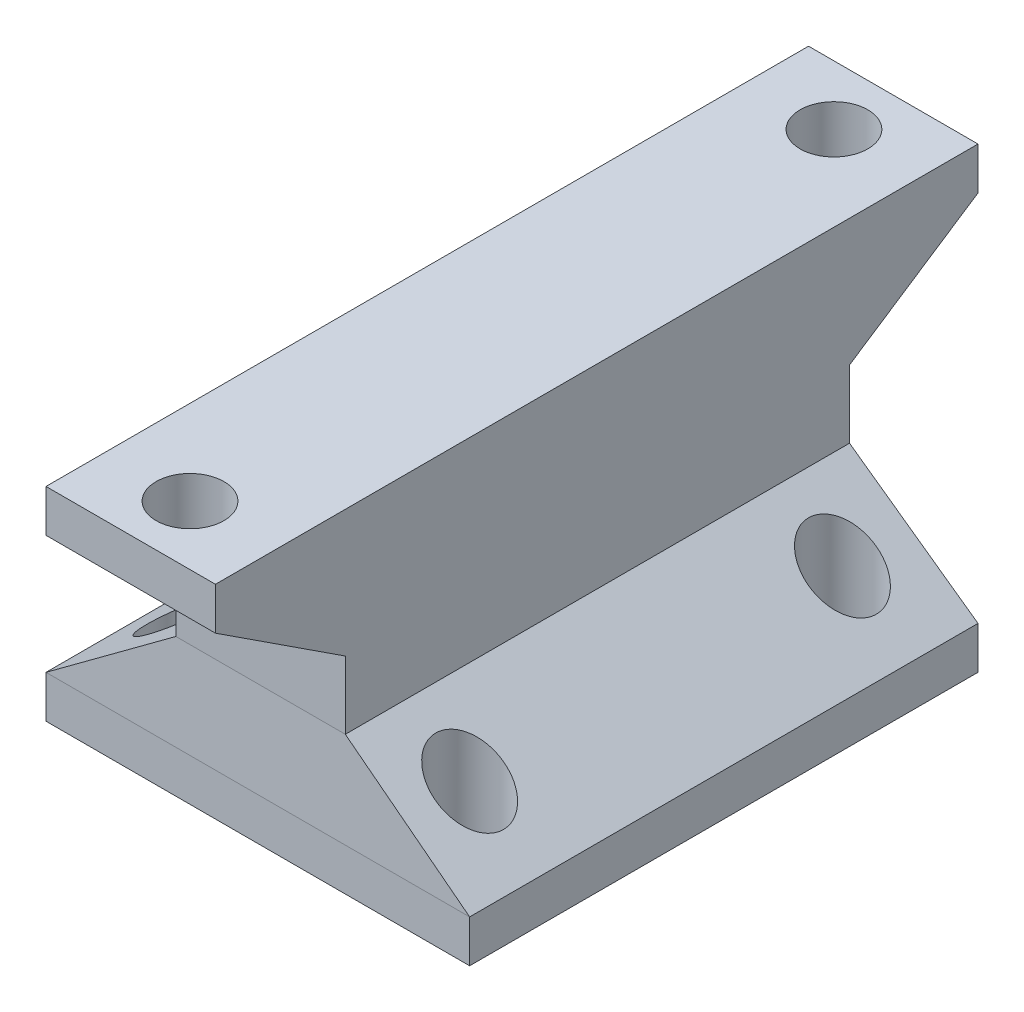
SolidWorks part; units mm, degrees
ref_plane "Front Plane" through (0, 0, 0) normal (0, 0, 1) x (1, 0, 0)
ref_plane "Top Plane" through (0, 0, 0) normal (0, 1, 0) x (1, 0, 0)
ref_plane "Right Plane" through (0, 0, 0) normal (1, 0, 0) x (0, 0, -1)
sketch "Sketch1" plane through (0, 0, 0) normal (0, 1, 0) x (1, 0, 0)
  line L1 (-10, 45) -> (10, 45)
  line L2 (-10, 45) -> (-10, -45)
  line L3 (-10, -45) -> (10, -45)
  line L4 (10, 45) -> (10, -45)
  line L5 (-10, 45) -> (10, -45) construction
  line L6 (-10, -45) -> (10, 45) construction
  point P0 (0, 0)
extrude "Boss-Extrude1" add sketch "Sketch1" along normal blind 5
sketch "Sketch2" plane through (10, 0, 0) normal (1, 0, 0) x (0, 0, -1)
  line L0 (-29.6724, -9.9997) -> (-45, 0)
  line L1 (-45, 0) -> (45, 0)
  line L5 (29.8362, -9.9997) -> (45, 0)
  line L6 (29.8362, -9.9997) -> (-29.6724, -9.9997)
  line L7 (0, 0) -> (0.0819, -9.9997)
  line M7 (-45, 0) -> (45, 0)
extrude "Boss-Extrude2" add sketch "Sketch2" against normal blind 20 contours L7 L0 L6 M7 | L1 L7 L6 L5
ref_plane "Plane1" through (0, -28.9997, 0) normal (0, -1, 0) x (-1, 0, 0)
sketch "Sketch3" plane through (0, -28.9997, 0) normal (0, -1, 0) x (-1, 0, 0)
  line L1 (-25, 30) -> (25, 30)
  line L2 (-25, 30) -> (-25, -30)
  line L3 (-25, -30) -> (25, -30)
  line L4 (25, 30) -> (25, -30)
  line L5 (-25, 30) -> (25, -30) construction
  line L6 (-25, -30) -> (25, 30) construction
  point P0 (0, 0)
extrude "Boss-Extrude3" add sketch "Sketch3" along normal blind 5 separate body
sketch "Sketch4" plane through (0, -33.9997, 0) normal (0, -1, 0) x (1, 0, 0)
  line L1 (-25, 30) -> (-17.08, 30)
  line L2 (-25, 30) -> (-25, 22)
  line L3 (-25, 22) -> (-17.08, 22)
  line L4 (-17.08, 30) -> (-17.08, 22)
  line L5 (25, 30) -> (17, 30)
  line L6 (25, 30) -> (25, 22)
  line L7 (25, 22) -> (17, 22)
  line L8 (17, 30) -> (17, 22)
  line L9 (-25, -30) -> (-17, -30)
  line L10 (-25, -30) -> (-25, -22)
  line L11 (-25, -22) -> (-17, -22)
  line L12 (-17, -30) -> (-17, -22)
  line L13 (25, -30) -> (17, -30)
  line L14 (25, -30) -> (25, -22)
  line L15 (25, -22) -> (17, -22)
  line L16 (17, -30) -> (17, -22)
  circle A0 centre (-17.08, 22) radius 4
  circle A1 centre (17, 22) radius 4
  circle A2 centre (-17, -22) radius 4
  circle A3 centre (17, -22) radius 4
sketch "Sketch5" plane through (0, 5, 0) normal (0, 1, 0) x (1, 0, 0)
  line L0 (0, 45) -> (0, 38)
  line L1 (10, 45) -> (-10, 45) construction
  line L2 (0, -45) -> (0, -38)
  line L3 (-10, -45) -> (10, -45) construction
  circle A0 centre (0, 38) radius 4
  circle A1 centre (0, -38) radius 4
sketch "Sketch6" plane through (0, -9.9997, 0) normal (0, -1, 0) x (1, 0, 0)
  line L1 (-10, 29.6724) -> (10, 29.6724)
  line L2 (-10, 29.6724) -> (-10, -29.8362)
  line L3 (-10, -29.8362) -> (10, -29.8362)
  line L4 (10, 29.6724) -> (10, -29.8362)
extrude "Boss-Extrude4" add sketch "Sketch6" along normal blind 8
loft "Loft3" add section face at (0, -28.9997, 0) section face at (0, -17.9997, -0.0819)
extrude "Cut-Extrude3" cut sketch "Sketch4" against normal blind 20 and the other way blind 10 contours L4 A0 L3 | L3 A0 L4 | L7 A1 L8 | L8 A1 L7 | L11 A2 L12 | L12 A2 L11 | L16 A3 L15 | L15 A3 L16
extrude "Cut-Extrude4" cut sketch "Sketch5" against normal blind 20
sketch "Sketch7" plane through (0, -33.9997, 0) normal (0, -1, 0) x (1, 0, 0)
  circle A0 centre (0, 0) radius 5
extrude "Cut-Extrude5" cut sketch "Sketch7" against normal blind 2
